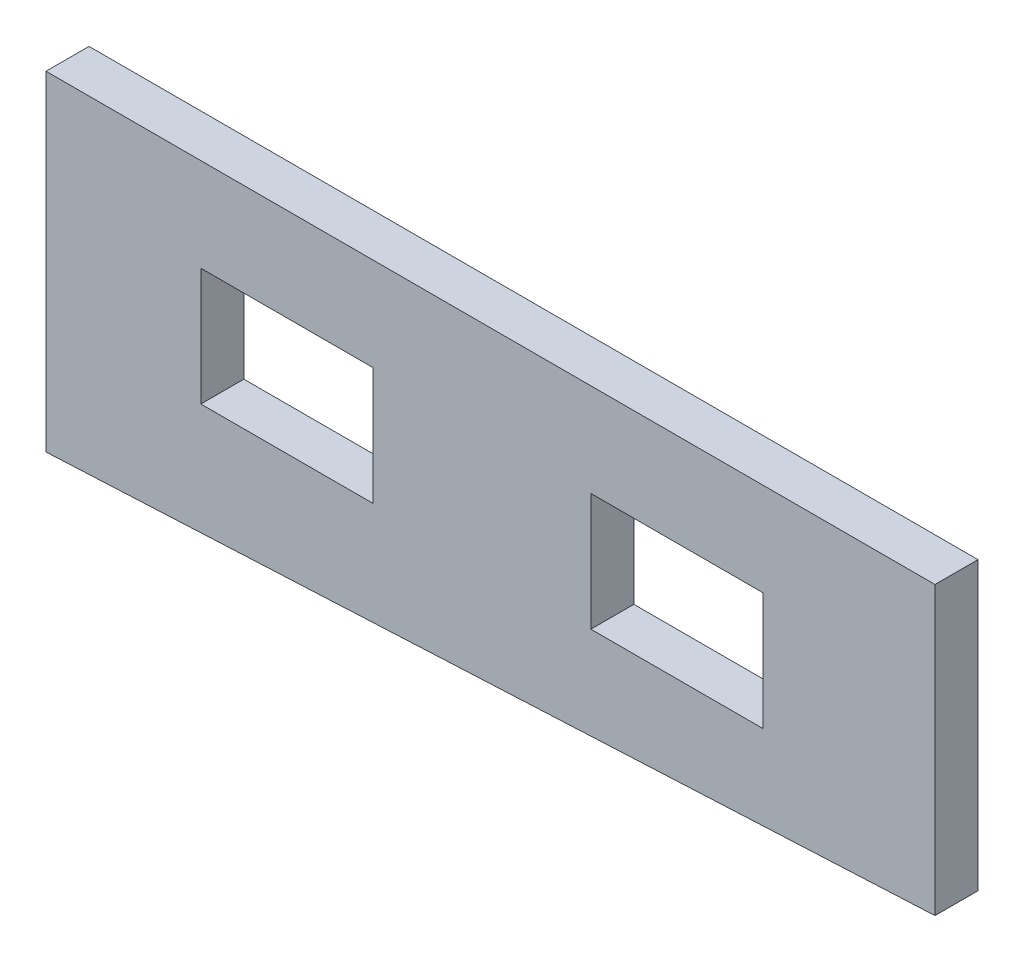
SolidWorks part; units mm, degrees
ref_plane "Front" through (0, 0, 0) normal (0, 0, 1) x (1, 0, 0)
ref_plane "Top" through (0, 0, 0) normal (0, 1, 0) x (1, 0, 0)
ref_plane "Right" through (0, 0, 0) normal (1, 0, 0) x (0, 0, -1)
sketch "Esquisse1" plane through (0, 0, 0) normal (0, 0, 1) x (1, 0, 0)
  line L0 (0, 0) -> (0, 2300)
  line L1 (0, 2300) -> (6200, 2300)
  line L2 (6200, 2300) -> (6200, 300)
  line L3 (6200, 300) -> (0, 0)
  dimension "D1" = 2300
  dimension "D2" = 2000
  dimension "D3" = 6200
extrude "Boss.-Extru.1" add sketch "Esquisse1" along normal blind 300
sketch "Esquisse2" plane through (0, 0, 300) normal (0, 0, 1) x (1, 0, 0)
  line L0 (0, 2300) -> (0, 0) construction
  line L1 (1080, 1650) -> (2280, 1650)
  line L2 (1080, 1650) -> (1080, 830)
  line L3 (1080, 830) -> (2280, 830)
  line L4 (2280, 1650) -> (2280, 830)
  line L5 (3800, 1650) -> (5000, 1650)
  line L6 (3800, 1650) -> (3800, 830)
  line L7 (3800, 830) -> (5000, 830)
  line L8 (5000, 1650) -> (5000, 830)
  dimension "D1" = 820
  dimension "D2" = 1200
  dimension "D3" = 1080
  dimension "D4" = 830
  dimension "D5" = 1520
extrude "Enlèv. mat.-Extru.1" cut sketch "Esquisse2" against normal through all
